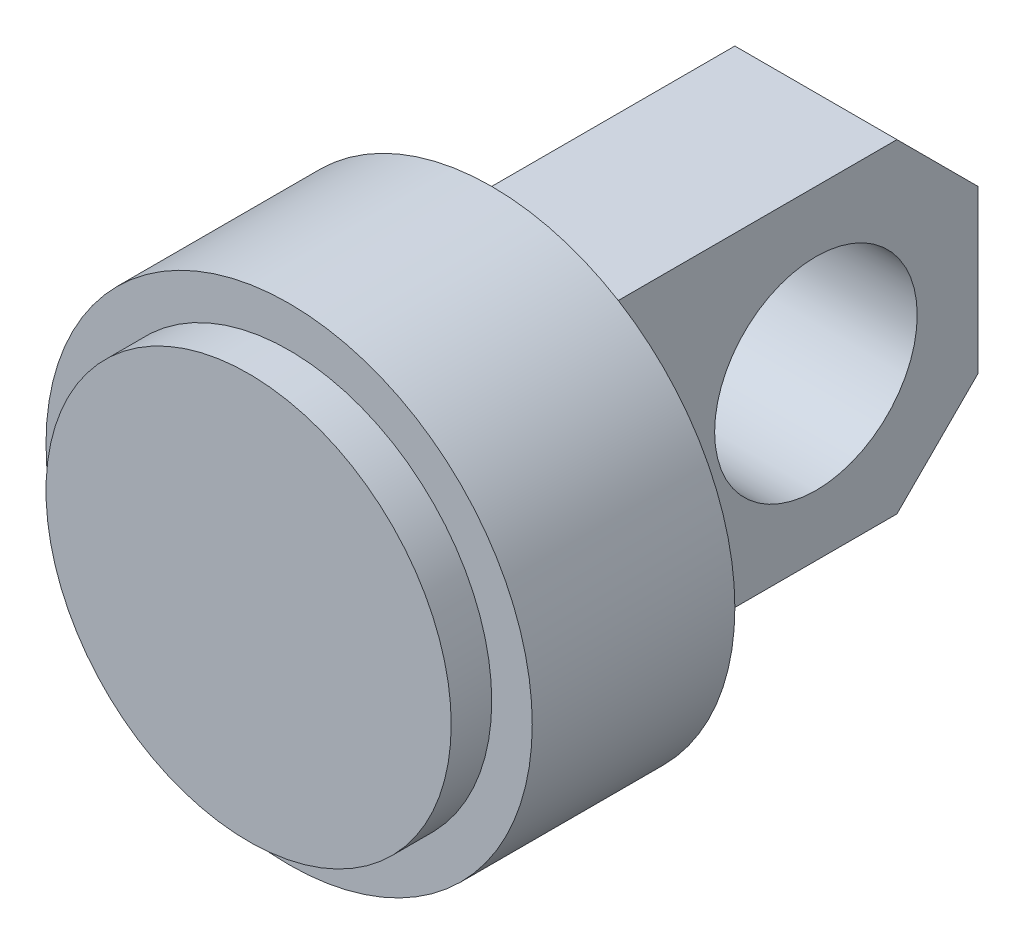
SolidWorks part; units mm, degrees
ref_plane "Front Plane" through (0, 0, 0) normal (0, 0, 1) x (1, 0, 0)
ref_plane "Top Plane" through (0, 0, 0) normal (0, 1, 0) x (1, 0, 0)
ref_plane "Right Plane" through (0, 0, 0) normal (1, 0, 0) x (0, 0, -1)
sketch "Sketch1" plane through (0, 0, 0) normal (0, 0, 1) x (1, 0, 0)
  circle A0 centre (0, 0) radius 25
  dimension "D1" = 50
extrude "Boss-Extrude1" add sketch "Sketch1" along normal blind 5
sketch "Sketch2" plane through (0, 0, 0) normal (0, 0, -1) x (-1, 0, 0)
  circle A0 centre (0, 0) radius 30
  dimension "D1" = 60
extrude "Boss-Extrude2" add sketch "Sketch2" along normal blind 25
sketch "Sketch3" plane through (0, 0, -25) normal (0, 0, -1) x (-1, 0, 0)
  line L1 (-10, -20) -> (10, -20)
  line L2 (-10, -20) -> (-10, 20)
  line L3 (-10, 20) -> (10, 20)
  line L4 (10, -20) -> (10, 20)
  line L5 (-10, -20) -> (10, 20) construction
  line L6 (-10, 20) -> (10, -20) construction
  point P0 (0, 0)
  dimension "D1" = 20
  dimension "D2" = 40
extrude "Boss-Extrude3" add sketch "Sketch3" along normal blind 50
chamfer "Chamfer1" distance 10 2 edges at (0, -20, -75) (0, 20, -75)
sketch "Sketch5" plane through (-10, 0, 0) normal (-1, 0, 0) x (0, 0, 1)
  line L1 (-75, -10) -> (-75, 10) construction
  line L2 (-65, 20) -> (-25, 20) construction
  circle A0 centre (-55, 0) radius 12.5
  dimension "D1" = 25
  dimension "D2" = 20
  dimension "D3" = 20
extrude "Cut-Extrude1" cut sketch "Sketch5" against normal through all
